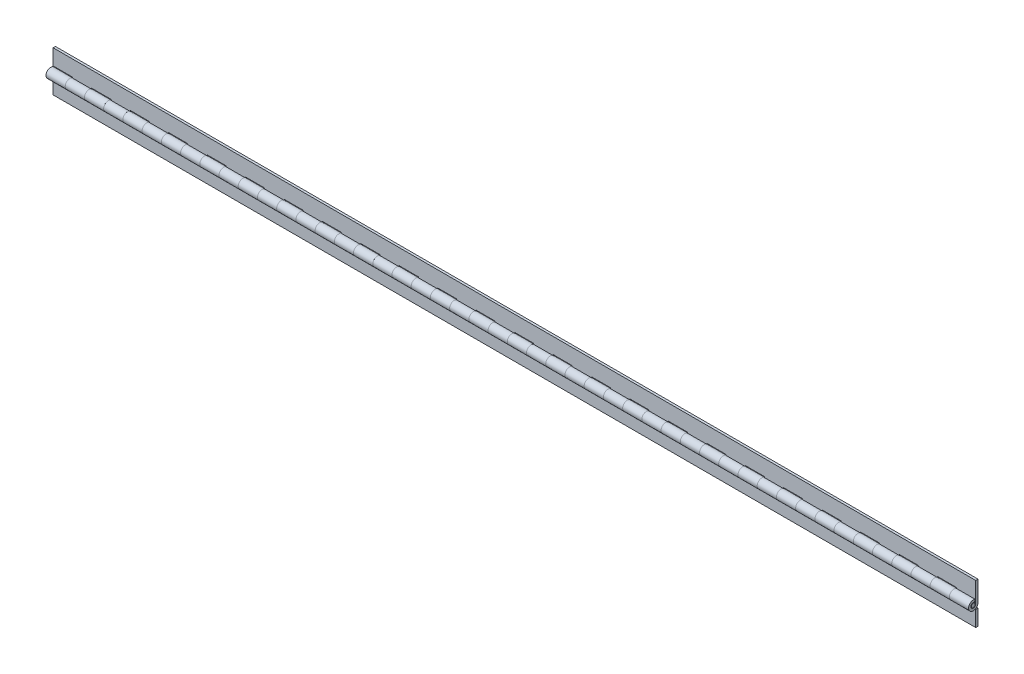
SolidWorks part; units mm, degrees
other "Bottom Leaf"
other "Top Leaf"
other "Pin" parameters "D1"=17.6771, "Angle"=25, "D2"=74.218, "Pin Diameter"=3.175, "D3"=51.2197, "Knuckle Diameter"=28.575, "Leaf Thickness"=1.524, "Overall Width"=26.9875, "Length"=609.6, "Break Line"=101.6, "Knuckle Length"=12.7, "Chamfer"=0.3175
ref_plane "Front Plane" through (0, 0, 0) normal (0, 0, 1) x (1, 0, 0)
ref_plane "Top Plane" through (0, 0, 0) normal (0, 1, 0) x (1, 0, 0)
ref_plane "Right Plane" through (0, 0, 0) normal (1, 0, 0) x (0, 0, -1)
sketch "Sketch1" plane through (0, 0, 0) normal (1, 0, 0) x (0, 0, -1)
  line L0 (3.1115, 0) -> (3.1115, -13.4937) construction
  line L1 (3.1115, -13.4937) -> (1.5875, -13.4937) construction
  line L2 (1.5875, -13.4937) -> (1.5875, -2.6761) construction
  line L3 (0, 1.5875) -> (0, 3.1115) construction
  line L4 (0.6709, 1.4388) -> (1.315, 2.82) construction
  line L5 (0, -1.5875) -> (0, -3.1115) construction
  line L6 (0.6709, -1.4388) -> (1.315, -2.82) construction
  line L7 (3.1115, 0) -> (3.1115, 13.4937) construction
  line L8 (3.1115, 13.4937) -> (1.5875, 13.4937) construction
  line L9 (1.5875, 13.4937) -> (1.5875, 2.6761) construction
  line L10 (0, 3.1115) -> (3.1115, 3.1115) construction
  line L11 (0, -3.1115) -> (3.1115, -3.1115) construction
  line L12 (1.5875, -2.6761) -> (1.5875, 2.6761) construction
  line L13 (1.5875, 3.1369) -> (3.1115, 3.1369) construction
  circle A0 centre (0, 0) radius 1.5875 construction
  circle A1 centre (0, 0) radius 3.1115 construction
  point P3 (0, 1.5875)
  point P4 (0, -1.5875)
  point P5 (-1.5875, 0)
  point P6 (1.5875, 0)
  point P8 (-3.1115, 0)
  point P9 (0, 3.1115)
  point P10 (3.1115, 0)
  point P11 (0, -3.1115)
  point P17 (1.5875, -13.4937)
  point P18 (3.1115, -13.4937)
  point P22 (1.5875, -2.6761)
  point P24 (0.6709, 1.4388)
  point P25 (1.315, 2.82)
  point P30 (0.6709, -1.4388)
  point P31 (1.315, -2.82)
  point P34 (1.5875, 2.6761)
  point P36 (1.5875, 13.4937)
  point P37 (3.1115, 13.4937)
  point P40 (3.1115, -3.1115)
  point P41 (3.1115, 3.1115)
  point P44 (1.5875, 3.1369)
  point P45 (3.1115, 3.1369)
  dimension "D1" = 25
  dimension "Knuckle Diameter" = 6.223
  dimension "D2" = 0.0254
sketch "Sketch2" plane through (0, 0, 0) normal (0, 0, 1) x (1, 0, 0)
  line L0 (304.8, 13.4937) -> (-304.8, 13.4937) construction
  line L2 (304.8, -13.4937) -> (-304.8, -13.4938) construction
  line L4 (-304.8, -13.4938) -> (-304.8, 13.4937) construction
  line L5 (304.8, -13.4937) -> (304.8, 13.4937) construction
  line L6 (304.8, 3.1115) -> (-304.8, 3.1115) construction
  line L7 (-304.8, -3.1115) -> (304.8, -3.1115) construction
  line L8 (304.8, 0) -> (-304.8, 0) construction
  line L9 (203.2, -13.4937) -> (203.2, 13.4937) construction
  line L10 (-203.2, -13.4938) -> (-203.2, 13.4937) construction
  line L11 (0, -13.4937) -> (0, 13.4937) construction
  line L12 (304.8, 2.794) -> (304.4825, 3.1115) construction
  point P4 (0, 13.4937)
  point P9 (0, -13.4937)
  point P10 (-304.8, -13.4938)
  point P12 (-304.8, 13.4937)
  point P13 (304.8, -13.4937)
  point P14 (304.8, 13.4937)
  point P18 (292.1, -3.1115)
  point P19 (-304.8, -3.1115)
  point P20 (-304.8, 3.1115)
  point P21 (304.8, -3.1115)
  point P22 (304.8, 3.1115)
  point P28 (0, 0)
  point P30 (-304.8, 0)
  point P31 (304.8, 0)
  point P34 (203.2, 0)
  point P35 (203.2, -13.4937)
  point P36 (203.2, 13.4937)
  point P39 (-203.2, 0)
  point P40 (-203.2, 13.4937)
  point P41 (-203.2, -13.4938)
  point P44 (0, 0)
  point P45 (279.4, -3.1115)
  point P49 (304.4825, 3.1115)
  point P50 (304.8, 2.794)
  dimension "D1" = 12.7
  dimension "D2" = 45
ref_plane "Plane1" through (304.8, 0, 0) normal (1, 0, 0) x (0, 0, -1)
sketch "Sketch3" plane through (0, 0, 0) normal (1, 0, 0) x (0, 0, -1)
  line L0 (1.5875, 0) -> (1.5875, -2.6761)
  line L2 (0.6709, -1.4388) -> (1.315, -2.82) construction
  line L3 (0.6709, -1.4388) -> (1.315, -2.82)
  line L4 (1.5875, -13.4937) -> (1.5875, -2.6761) construction
  line L5 (1.5875, -13.4937) -> (1.5875, -2.6761)
  line L6 (3.1115, 0) -> (3.1115, -13.4937) construction
  line L7 (3.1115, 0) -> (3.1115, -13.4937)
  line L8 (3.1115, -13.4937) -> (1.5875, -13.4937) construction
  line L9 (3.1115, -13.4937) -> (1.5875, -13.4937)
  circle A0 centre (0, 0) radius 3.1115 construction
  arc A1 (3.1115, 0) -> (1.315, -2.82) centre (0, 0) ccw
  circle A2 centre (0, 0) radius 1.5875 construction
  arc A3 (1.5875, 0) -> (0.6709, -1.4388) centre (0, 0) ccw
extrude "Boss-Extrude1" add sketch "Sketch3" along normal mid plane 609.6
sketch "Sketch4" plane through (0, 0, 0) normal (0, 0, 1) x (1, 0, 0)
  line L0 (292.1, -3.1115) -> (292.1, 3.1115)
  line L1 (304.8, 3.1115) -> (-304.8, 3.1115) construction
  line L2 (292.1, 3.1115) -> (304.8, 3.1115)
  line L3 (304.8, 3.1115) -> (304.8, -3.1115)
  line L4 (304.8, -3.1115) -> (292.1, -3.1115)
extrude "Cut-Extrude1" cut sketch "Sketch4" against normal through all both and the other way through all
pattern_linear "LPattern1" count 24 spacing 25.4 along (-1, 0, 0) of "Cut-Extrude1"
sketch "Sketch5" plane through (304.8, 0, 0) normal (1, 0, 0) x (0, 0, -1)
  line L0 (1.5875, 13.4937) -> (1.5875, 2.6761) construction
  line L1 (3.1115, 0) -> (3.1115, 13.4937) construction
  line L3 (1.5875, 13.4937) -> (1.5875, 2.6761)
  line L4 (3.1115, 0) -> (3.1115, 13.4937)
  line L6 (3.1115, 13.4937) -> (1.5875, 13.4937) construction
  line L7 (3.1115, 13.4937) -> (1.5875, 13.4937)
  line L8 (0.6709, 1.4388) -> (1.315, 2.82) construction
  line L9 (0.6709, 1.4388) -> (1.315, 2.82)
  line L10 (1.5875, 2.6761) -> (1.5875, 0)
  circle A0 centre (0, 0) radius 1.5875 construction
  circle A1 centre (0, 0) radius 3.1115 construction
  arc A2 (0.6709, 1.4388) -> (1.5875, 0) centre (0, 0) ccw
  arc A3 (1.315, 2.82) -> (3.1115, 0) centre (0, 0) ccw
extrude "Boss-Extrude2" add sketch "Sketch5" against normal blind 609.6 separate body
sketch "Sketch6" plane through (0, 0, 0) normal (0, 0, 1) x (1, 0, 0)
  line L0 (279.4, -3.1115) -> (279.4, 3.1115)
  line L1 (304.8, 3.1115) -> (-304.8, 3.1115) construction
  line L2 (279.4, 3.1115) -> (292.1, 3.1115)
  line L3 (292.1, 3.1115) -> (292.1, -3.1115)
  line L4 (292.1, -3.1115) -> (279.4, -3.1115)
extrude "Cut-Extrude2" cut sketch "Sketch6" against normal through all both and the other way through all
pattern_linear "LPattern2" count 24 spacing 25.4 along (-1, 0, 0) of "Cut-Extrude2"
sketch "Sketch7" plane through (304.8, 0, 0) normal (1, 0, 0) x (0, 0, -1)
  circle A0 centre (0, 0) radius 1.5875 construction
  circle A1 centre (0, 0) radius 1.5875
extrude "Boss-Extrude3" add sketch "Sketch7" against normal blind 609.6 separate body
chamfer "Chamfer1" distance 0.3175 angle 45 2 edges at (-304.8, 0, -1.5875) (304.8, 0, -1.5875)
equation "\"D1@Sketch1\"=\"Angle@Sketch1\""
equation "\"D1@Sketch2\"=\"Knuckle Length@Sketch2\""
equation "\"D1@Boss-Extrude1\" = \"Length@Sketch2\""
equation "\"D1@LPattern1\" = \"Length@Sketch2\" /  ( \"Knuckle Length@Sketch2\" * 2 ) "
equation "\"D3@LPattern1\" = \"Knuckle Length@Sketch2\" * 2"
equation "\"D1@Boss-Extrude2\"=\"Length@Sketch2\""
equation "\"Chamfer@Sketch2\" = \"Pin Diameter@Sketch1\" * .1"
equation "\"D1@Boss-Extrude3\" = \"Length@Sketch2\""
equation "\"D1@Chamfer1\"=\"Chamfer@Sketch2\""
equation "\"D3@LPattern2\" = \"Knuckle Length@Sketch2\" * 2"
equation "\"D1@LPattern2\" = \"Length@Sketch2\" /  ( \"Knuckle Length@Sketch2\" * 2 ) "
